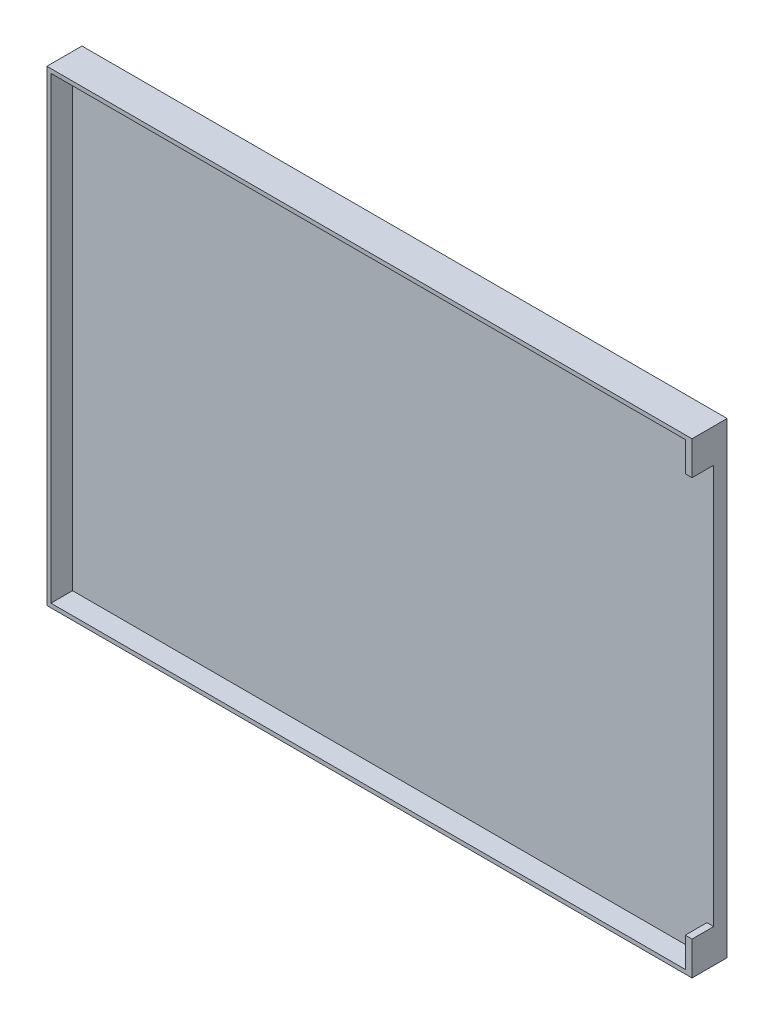
SolidWorks part; units mm, degrees
ref_plane "Спереди" through (0, 0, 0) normal (0, 0, 1) x (1, 0, 0)
ref_plane "Сверху" through (0, 0, 0) normal (0, 1, 0) x (1, 0, 0)
ref_plane "Справа" through (0, 0, 0) normal (1, 0, 0) x (0, 0, -1)
sketch "Эскиз1" plane through (0, 0, 0) normal (0, 0, 1) x (1, 0, 0)
  line L1 (-23.9, -17.3) -> (23.9, -17.3)
  line L2 (-23.9, -17.3) -> (-23.9, 17.3)
  line L3 (-23.9, 17.3) -> (23.9, 17.3)
  line L4 (23.9, -17.3) -> (23.9, 17.3)
  line L5 (-23.9, -17.3) -> (23.9, 17.3) construction
  line L6 (-23.9, 17.3) -> (23.9, -17.3) construction
  point P0 (0, 0)
  dimension "D1" = 34.6
  dimension "D2" = 47.8
extrude "Бобышка-Вытянуть1" add sketch "Эскиз1" along normal blind 1
sketch "Эскиз2" plane through (0, 0, 1) normal (0, 0, 1) x (1, 0, 0)
  line L4 (23.9, -17.3) -> (23.9, 17.3)
  line L5 (23.9, 17.3) -> (-23.9, 17.3)
  line L6 (-23.9, 17.3) -> (-23.9, -17.3)
  line L7 (-23.9, -17.3) -> (23.9, -17.3)
  line L9 (23.9, 17.3) -> (-23.9, 17.3)
  line L10 (-23.9, 17.3) -> (-23.9, -17.3)
  line L11 (-23.9, -17.3) -> (23.9, -17.3)
  line L12 (23.4, 17) -> (-23.6, 17)
  line L13 (-23.6, 17) -> (-23.6, -17)
  line L14 (-23.6, -17) -> (23.4, -17)
  line L15 (23.9, 17) -> (-23.6, 17) construction
  line L16 (-23.6, -17) -> (23.9, -17) construction
  line L17 (23.4, 17) -> (23.4, 14.8)
  line L18 (23.4, 14.8) -> (23.9, 14.8)
  line L19 (23.9, -17.3) -> (23.9, 17.3) construction
  line L20 (23.9, 14.8) -> (23.9, 17.3)
  line L21 (23.4, -17) -> (23.4, -14.8)
  line L22 (23.4, -14.8) -> (23.9, -14.8)
  line L23 (23.9, -14.8) -> (23.9, -17.3)
  dimension "D3" = 0.5
  dimension "D4" = 2.5
  dimension "D1" = 0
  dimension "D2" = 0.3
extrude "Бобышка-Вытянуть2" add sketch "Эскиз2" along normal blind 1.6
